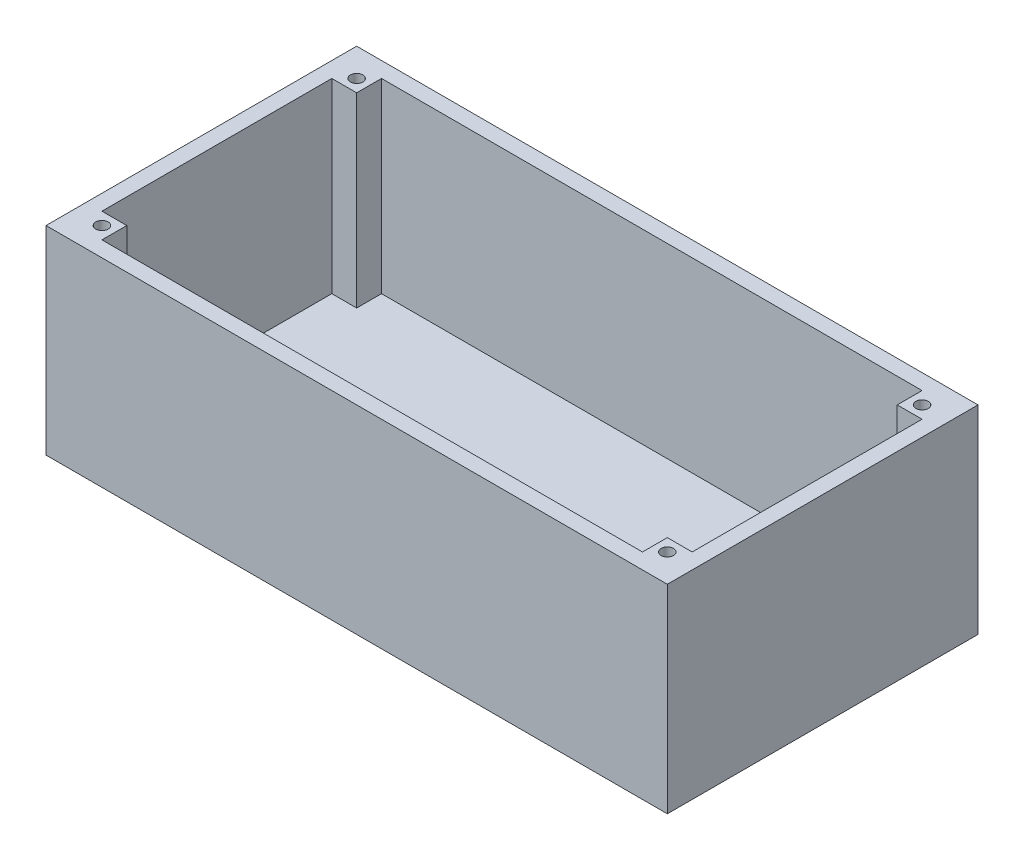
SolidWorks part; units mm, degrees
ref_plane "Front Plane" through (0, 0, 0) normal (0, 0, 1) x (1, 0, 0)
ref_plane "Top Plane" through (0, 0, 0) normal (0, 1, 0) x (1, 0, 0)
ref_plane "Right Plane" through (0, 0, 0) normal (1, 0, 0) x (0, 0, -1)
sketch "Sketch1" plane through (0, 0, 0) normal (0, 1, 0) x (1, 0, 0)
  line L1 (0, 0) -> (100, 0)
  line L2 (0, 0) -> (0, 50)
  line L3 (0, 50) -> (100, 50)
  line L4 (100, 0) -> (100, 50)
  dimension "D1" = 100
  dimension "D2" = 50
extrude "Boss-Extrude1" add sketch "Sketch1" along normal blind 2
sketch "Sketch3" plane through (0, 2, 0) normal (0, 1, 0) x (1, 0, 0)
  line L1 (0, 50) -> (100, 50)
  line L2 (0, 50) -> (0, 0)
  line L3 (0, 0) -> (100, 0)
  line L4 (100, 50) -> (100, 0)
  line L5 (6.5, 47.5) -> (93.5, 47.5)
  line L6 (2.5, 43.5) -> (2.5, 6.5)
  line L7 (6.5, 2.5) -> (93.5, 2.5)
  line L8 (97.5, 43.5) -> (97.5, 6.5)
  line L11 (2.5, 43.5) -> (6.5, 43.5)
  line L12 (6.5, 47.5) -> (6.5, 43.5)
  line L14 (97.5, 43.5) -> (93.5, 43.5)
  line L15 (93.5, 47.5) -> (93.5, 43.5)
  line L16 (97.5, 6.5) -> (93.5, 6.5)
  line L17 (93.5, 2.5) -> (93.5, 6.5)
  line L18 (6.5, 2.5) -> (6.5, 6.5)
  line L19 (2.5, 6.5) -> (6.5, 6.5)
  line L20 (6.5, 47.5) -> (2.5, 43.5) construction
  circle A0 centre (4.5, 45.5) radius 1
  circle A1 centre (95.5, 45.5) radius 1
  circle A2 centre (95.5, 4.5) radius 1
  circle A3 centre (4.5, 4.5) radius 1
  dimension "D7" = 2
  dimension "D8" = 2
  dimension "D1" = 2.5
  dimension "D2" = 2.5
  dimension "D3" = 2.5
  dimension "D4" = 2.5
  dimension "D5" = 4
  dimension "D6" = 4
  dimension "D9" = 2
extrude "Boss-Extrude2" add sketch "Sketch3" along normal blind 30
sketch "Sketch4" plane through (0, 2, 0) normal (0, 1, 0) x (1, 0, 0)
  line L0 (0, 0) -> (0, 29.9) construction
  line L1 (0, 50) -> (0, 0) construction
  point P5 (0, 15.9)
  dimension "D1" = 29.9
  dimension "D2" = 15.9
